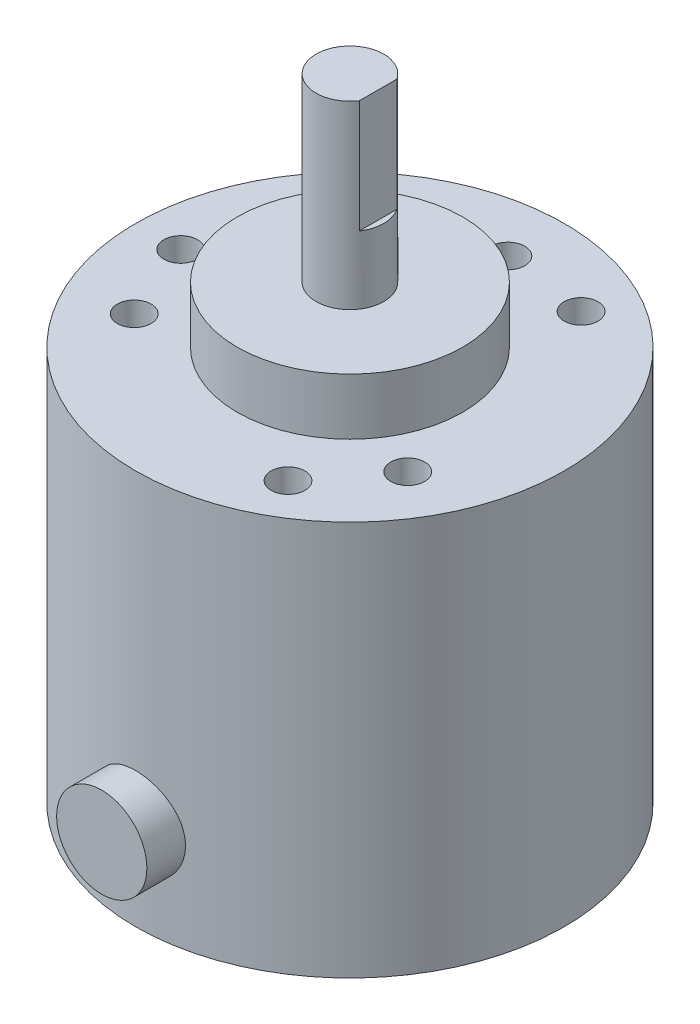
SolidWorks part; units mm, degrees
ref_plane "Front Plane" through (0, 0, 0) normal (0, 0, 1) x (1, 0, 0)
ref_plane "Top Plane" through (0, 0, 0) normal (0, 1, 0) x (1, 0, 0)
ref_plane "Right Plane" through (0, 0, 0) normal (1, 0, 0) x (0, 0, -1)
sketch "Sketch2" plane through (0, 0, 0) normal (0, 1, 0) x (1, 0, 0)
  circle A0 centre (0, 0) radius 19
  dimension "D1" = 38
extrude "Boss-Extrude2" add sketch "Sketch2" against normal blind 35 contours A0
sketch "Sketch4" plane through (0, 0, 0) normal (0, 1, 0) x (1, 0, 0)
  circle A0 centre (0, 0) radius 10
  dimension "D1" = 20
extrude "Boss-Extrude3" add sketch "Sketch4" along normal blind 5
sketch "Sketch5" plane through (0, 5, 0) normal (0, 1, 0) x (1, 0, 0)
  circle A0 centre (0, 0) radius 3
  dimension "D1" = 6
extrude "Boss-Extrude4" add sketch "Sketch5" along normal blind 16
sketch "Sketch8" plane through (0, 21, 0) normal (0, 1, 0) x (1, 0, 0)
  line L5 (3, -3.1414) -> (2.5, -3.1414)
  line L6 (3, -3.1414) -> (3, 2.9748)
  line L7 (3, 2.9748) -> (2.5, 2.9748)
  line L8 (2.5, -3.1414) -> (2.5, 2.9748)
  circle A1 centre (0, 0) radius 3 construction
  dimension "D1" = 0.5
extrude "Cut-Extrude2" cut sketch "Sketch8" against normal blind 10
sketch "Sketch10" plane through (0, 0, 0) normal (0, 1, 0) x (1, 0, 0)
  circle A0 centre (0, 0) radius 15
  circle A1 centre (0, 0) radius 14
  circle A2 centre (-15, 0) radius 1.5
  circle A3 centre (0, 14) radius 1.5
  circle A4 centre (7.5, 12.9904) radius 1.5
  circle A5 centre (7.5, -12.9904) radius 1.5
  circle A6 centre (12.1244, -7) radius 1.5
  circle A7 centre (-12.1244, -7) radius 1.5
  circle A8 centre (0, 0) radius 10 construction
  point P4 (-15, 0)
  point P14 (0, 0)
  point P18 (-12.1244, -7)
  point P20 (0, 0)
  point P29 (-16.4737, -0.2796)
  point P31 (-15, 0)
  dimension "D1" = 30
  dimension "D2" = 28
  dimension "D3" = 3
  dimension "D4" = 3
  dimension "D5" = 3
  dimension "D6" = 3
extrude "Cut-Extrude3" cut sketch "Sketch10" against normal blind 7 contours A2 | A7 | A3 | A4 | A6 | A5
sketch "Sketch15" plane through (0, 0, 0) normal (0, 0, 1) x (1, 0, 0)
  circle A0 centre (0, -27) radius 4
  dimension "D2" = 8
extrude "Boss-Extrude5" add sketch "Sketch15" along normal blind 22 contours A0
